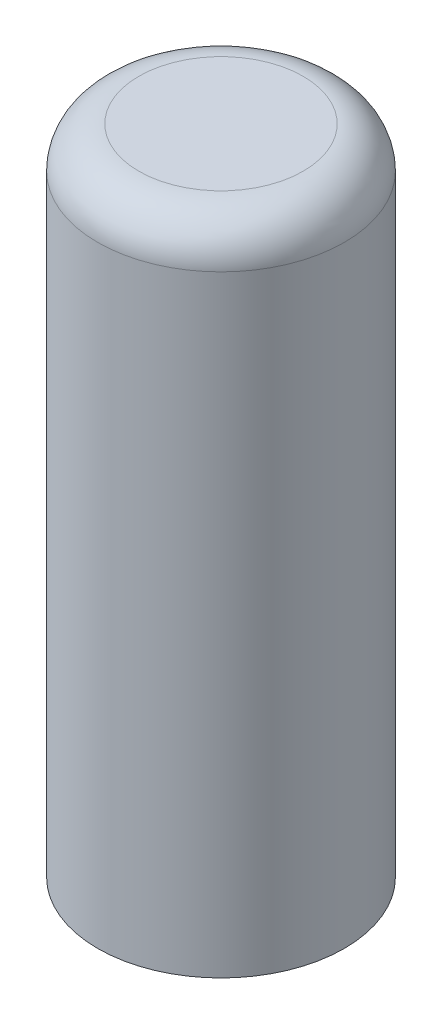
SolidWorks part; units mm, degrees
material "ABS"
ref_plane "Front" through (0, 0, 0) normal (0, 0, 1) x (1, 0, 0)
ref_plane "Top" through (0, 0, 0) normal (0, 1, 0) x (1, 0, 0)
ref_plane "Right" through (0, 0, 0) normal (1, 0, 0) x (0, 0, -1)
sketch "Sketch1" plane through (0, 0, 0) normal (0, 1, 0) x (1, 0, 0)
  circle A0 centre (0, 0) radius 1.5
  dimension "D1" = 3
extrude "Boss-Extrude1" add sketch "Sketch1" along normal blind 7.9375
fillet "Fillet1" radius 0.5 1 edges at (0, 7.9375, 1.5)
